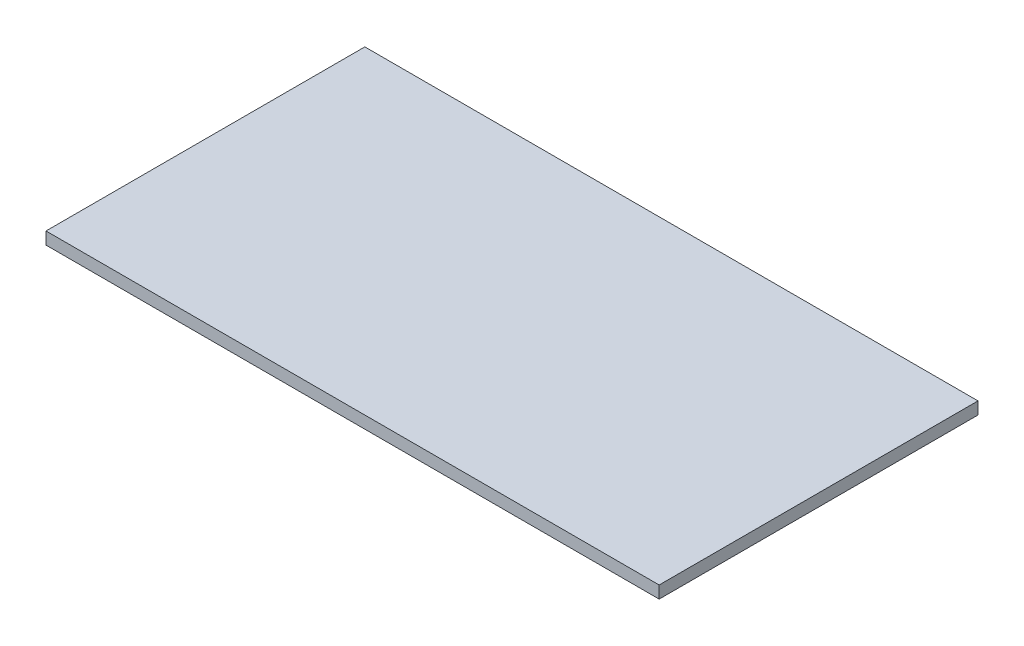
SolidWorks part; units mm, degrees
ref_plane "Front Plane" through (0, 0, 0) normal (0, 0, 1) x (1, 0, 0)
ref_plane "Top Plane" through (0, 0, 0) normal (0, 1, 0) x (1, 0, 0)
ref_plane "Right Plane" through (0, 0, 0) normal (1, 0, 0) x (0, 0, -1)
sketch "Sketch1" plane through (0, 0, 0) normal (0, 1, 0) x (1, 0, 0)
  line L1 (0, 0) -> (200, 0)
  line L2 (0, 0) -> (0, 104)
  line L3 (0, 104) -> (200, 104)
  line L4 (200, 0) -> (200, 104)
extrude "Boss-Extrude1" add sketch "Sketch1" along normal blind 4
